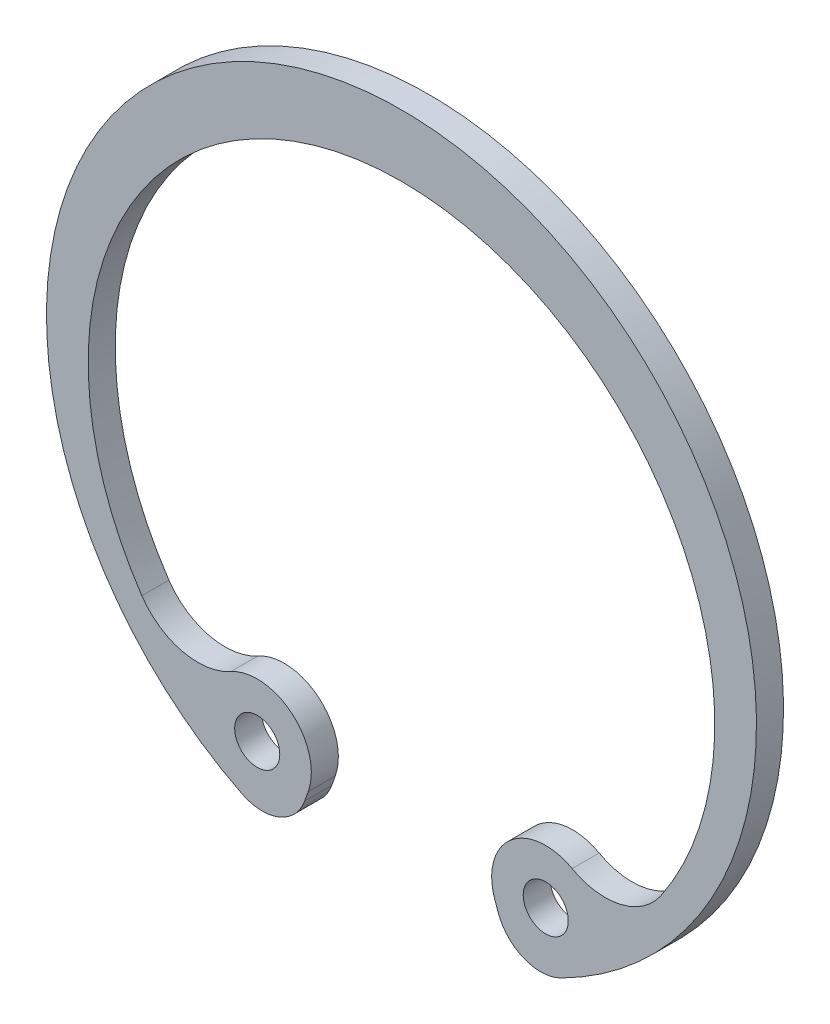
SolidWorks part; units mm, degrees
ref_plane "Спереди" through (0, 0, 0) normal (0, 0, 1) x (1, 0, 0)
ref_plane "Сверху" through (0, 0, 0) normal (0, 1, 0) x (1, 0, 0)
ref_plane "Справа" through (0, 0, 0) normal (1, 0, 0) x (0, 0, -1)
sketch "Clipboard" plane through (0, 0, 0) normal (0, 0, 1) x (1, 0, 0)
  circle A0 centre (0, 0) radius 15
  dimension "D1" = 30
sketch "Sketch1" plane through (0, 0, 0) normal (0, 0, 1) x (1, 0, 0)
  line L0 (0, -32.7005) -> (0, 29.6631) construction
  line L1 (4.1391, -11.6212) -> (4.2937, -12.0551)
  line L4 (-4.1391, -11.6212) -> (-4.2937, -12.0551)
  line L5 (0, 0) -> (-6.179, -17.3485) construction
  arc A0 (-7.0763, -13.1708) -> (7.0763, -13.1708) centre (0, 0.9) cw
  arc A1 (-7.0763, -13.1708) -> (-4.2937, -12.0551) centre (-6.1777, -11.3841) ccw
  arc A2 (-7.5506, -12.9221) -> (-4.1391, -11.6212) centre (-6.4, -10.8159) ccw construction
  arc A3 (-11.5186, -7.7803) -> (-7.57, -8.7204) centre (-9.0325, -6.1011) ccw
  arc A4 (7.0763, -13.1708) -> (4.2937, -12.0551) centre (6.1777, -11.3841) cw
  arc A5 (4.1391, -11.6212) -> (7.57, -8.7204) centre (6.4, -10.8159) cw
  arc A6 (11.5186, -7.7803) -> (7.57, -8.7204) centre (9.0325, -6.1011) cw
  arc A7 (-4.1391, -11.6212) -> (-7.57, -8.7204) centre (-6.4, -10.8159) ccw
  circle A8 centre (-6.4, -10.8159) radius 1
  circle A9 centre (6.4, -10.8159) radius 1
  arc A11 (11.5186, -7.7803) -> (-11.5186, -7.7803) centre (0, 0) ccw
  point P15 (-8.7994, -10.7602)
  dimension "D2" = 27.8
  dimension "D3" = 31.5
  dimension "D4" = 2
  dimension "R1" = 3
  dimension "R2" = 2
  dimension "a" = 4.8
  dimension "L" = 8
  dimension "e" = 0.9
  dimension "b" = 2.75
extrude "Body" add sketch "Sketch1" along normal blind 1.2
